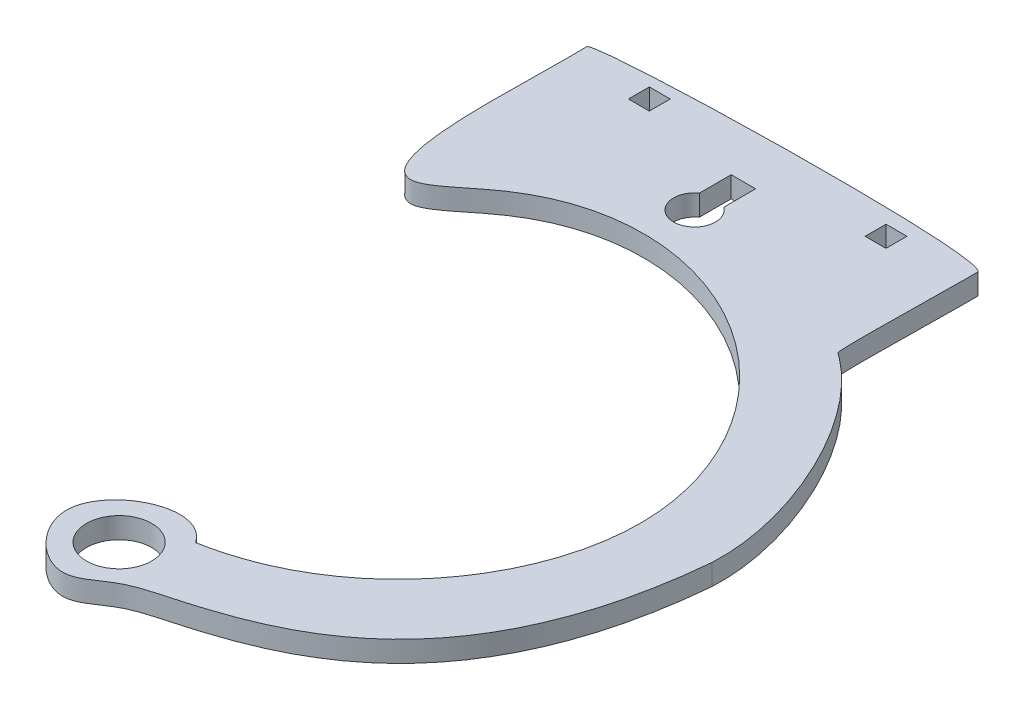
SolidWorks part; units mm, degrees
ref_plane "Front Plane" through (0, 0, 0) normal (0, 0, 1) x (1, 0, 0)
ref_plane "Top Plane" through (0, 0, 0) normal (0, 1, 0) x (1, 0, 0)
ref_plane "Right Plane" through (0, 0, 0) normal (1, 0, 0) x (0, 0, -1)
sketch "Sketch1" plane through (0, 0, 0) normal (0, 1, 0) x (1, 0, 0)
  line L1 (28, 35) -> (-28, 35) construction
  line L2 (28, 35) -> (28, 55) construction
  line L3 (28, 55) -> (-28, 55) construction
  line L4 (-28, 35) -> (-28, 55) construction
  line L5 (28, 35) -> (-28, 55) construction
  line L6 (28, 55) -> (-28, 35) construction
  circle A0 centre (0, 0) radius 40 construction
  circle A1 centre (0, -40) radius 4.75 construction
  circle A2 centre (0, -40) radius 7.75 construction
  circle A3 centre (0, 0) radius 35 construction
  circle A4 centre (0, 0) radius 45 construction
  spline S0 degree 3 poles (5.5216, -34.5617) (23.441, -31.4117) (44.4624, -2.8588) (20.375, 35.3512) (-9.4073, 38.5435) (-30.2262, 17.9966) (-27.7225, 45.3475) (-28.0432, 56.5042) (28.011, 57.688) (27.9669, 46.9503) (27.6537, 35.2407) (37.5515, 28.3605) (45.5872, 11.4498) (45, 0) knots 0 0 0 0 0.082838 0.148739 0.208271 0.224101 0.277627 0.277627 0.285968 0.285968 0.310948 0.310948 1 1 1 1
  spline S1 degree 3 poles (45, 0) (41.8351, -33.8354) (19.7672, -40.7526) (4.4778, -44.8709) (-0.8161, -50.4606) (-14.2628, -37.3252) (1.7546, -29.0679) (5.5216, -34.5617) knots 0 0 0 0 0.439042 0.498131 0.590884 0.751564 1 1 1 1
  point P8 (0, 45)
  dimension "D1" = 80
  dimension "D2" = 9.5
  dimension "D3" = 15.5
  dimension "D4" = 70
  dimension "D5" = 90
  dimension "D6" = 20
  dimension "D7" = 56
extrude "Boss-Extrude1" add sketch "Sketch1" along normal blind 3
sketch "Sketch2" plane through (0, 3, 0) normal (0, 1, 0) x (1, 0, 0)
  circle A0 centre (0, 0) radius 40 construction
  circle A1 centre (0, -40) radius 4.675
  dimension "D1" = 80
  dimension "D2" = 9.35
extrude "Cut-Extrude1" cut sketch "Sketch2" against normal blind 3
sketch "Sketch4" plane through (0, 3, 0) normal (0, 1, 0) x (1, 0, 0)
  circle A0 centre (0, 42.4718) radius 3
  dimension "D1" = 6
extrude "Cut-Extrude2" cut sketch "Sketch4" against normal blind 6
sketch "Sketch5" plane through (0, 3, 0) normal (0, 1, 0) x (1, 0, 0)
  line L1 (1.75, 41.4718) -> (-1.75, 41.4718)
  line L2 (1.75, 41.4718) -> (1.75, 49.4718)
  line L3 (1.75, 49.4718) -> (-1.75, 49.4718)
  line L4 (-1.75, 41.4718) -> (-1.75, 49.4718)
  line L5 (1.75, 41.4718) -> (-1.75, 49.4718) construction
  line L6 (1.75, 49.4718) -> (-1.75, 41.4718) construction
  circle A0 centre (0, 42.4718) radius 3 construction
  point P0 (0, 45.4718)
  dimension "D1" = 3.5
  dimension "D2" = 8
extrude "Cut-Extrude3" cut sketch "Sketch5" against normal blind 6
extrude "Cut-Extrude4" cut sketch "Sketch7" against normal through all
sketch "Sketch7" plane through (-39.0317, 3, -85.075) normal (0, 1, 0) x (1, 0, 0.0023)
  line L1 (20.5911, -30.5235) -> (23.5911, -30.5235)
  line L2 (20.5911, -30.5235) -> (20.5911, -33.5235)
  line L3 (20.5911, -33.5235) -> (23.5911, -33.5235)
  line L4 (23.5911, -30.5235) -> (23.5911, -33.5235)
  line L7 (54.5911, -33.5235) -> (57.5911, -33.5235)
  line L8 (54.5911, -33.5235) -> (54.5911, -30.5235)
  line L9 (54.5911, -30.5235) -> (57.5911, -30.5235)
  line L10 (57.5911, -33.5235) -> (57.5911, -30.5235)
equation "\"D3@Sketch1\"=9.5+6"
